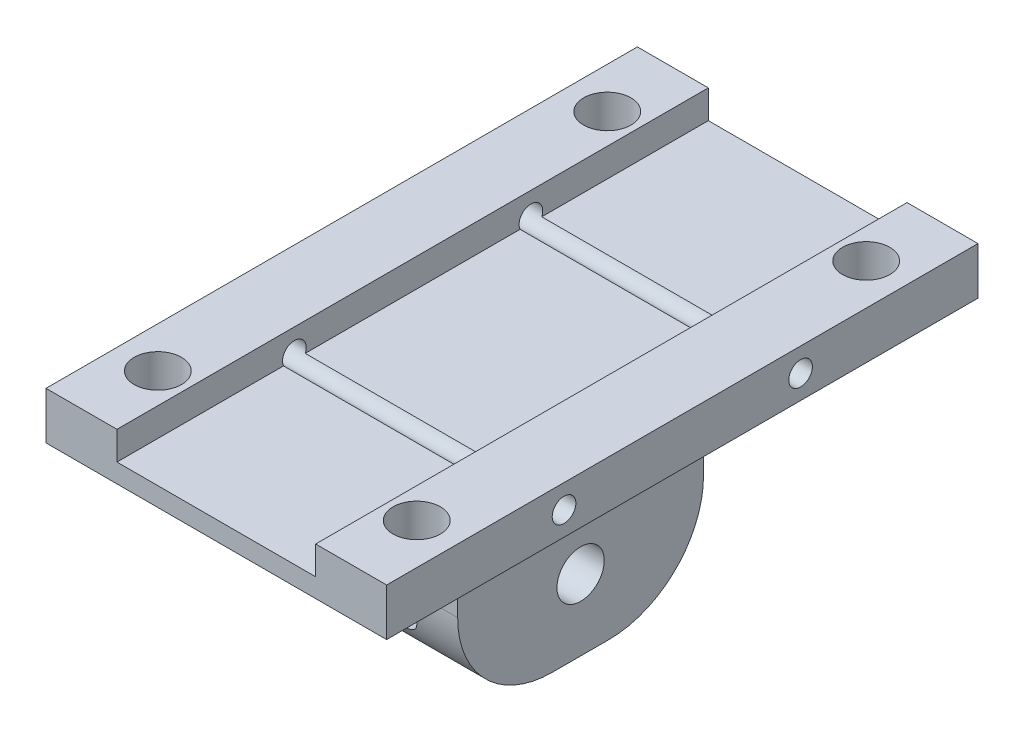
SolidWorks part; units mm, degrees
ref_plane "Front Plane" through (0, 0, 0) normal (0, 0, 1) x (1, 0, 0)
ref_plane "Top Plane" through (0, 0, 0) normal (0, 1, 0) x (1, 0, 0)
ref_plane "Right Plane" through (0, 0, 0) normal (1, 0, 0) x (0, 0, -1)
sketch "Sketch1" plane through (0, 0, 0) normal (1, 0, 0) x (0, 0, -1)
  line L0 (25.9808, -15) -> (25.9808, 15)
  line L1 (25.9808, 15) -> (-25.9808, 15)
  line L2 (-25.9808, 15) -> (-25.9808, -15)
  line L3 (-25.9808, -15) -> (25.9808, -15)
  circle A0 centre (0, 0) radius 5
extrude "Boss-Extrude1" add sketch "Sketch1" along normal mid plane 29
sketch "Sketch2" plane through (0, 15, 0) normal (0, 1, 0) x (1, 0, 0)
  line L4 (-14.5, 25.9808) -> (-14.5, -25.9808)
  line L5 (-14.5, -25.9808) -> (14.5, -25.9808)
  line L6 (14.5, -25.9808) -> (14.5, 25.9808)
  line L7 (14.5, 25.9808) -> (-14.5, 25.9808)
  line L8 (-14.5, 25.9808) -> (-14.5, -25.9808)
  line L9 (-14.5, -25.9808) -> (14.5, -25.9808)
  line L10 (14.5, -25.9808) -> (14.5, 25.9808)
  line L11 (14.5, 25.9808) -> (-14.5, 25.9808)
  dimension "D1" = 0
extrude "Boss-Extrude2" add sketch "Sketch2" along normal blind 15
sketch "Sketch3" plane through (0, 30, 0) normal (0, 1, 0) x (1, 0, 0)
  line L1 (-36, -62.5) -> (36, -62.5)
  line L2 (-36, -62.5) -> (-36, 62.5)
  line L3 (-36, 62.5) -> (36, 62.5)
  line L4 (36, -62.5) -> (36, 62.5)
  line L5 (-36, -62.5) -> (36, 62.5) construction
  line L6 (-36, 62.5) -> (36, -62.5) construction
  line L7 (-27.36, -47.5) -> (27.36, -47.5) construction
  line L8 (-27.36, -47.5) -> (-27.36, 47.5) construction
  line L9 (-27.36, 47.5) -> (27.36, 47.5) construction
  line L10 (27.36, -47.5) -> (27.36, 47.5) construction
  line L11 (-27.36, -47.5) -> (27.36, 47.5) construction
  line L12 (-27.36, 47.5) -> (27.36, -47.5) construction
  circle A0 centre (-27.36, 47.5) radius 5
  circle A1 centre (27.36, 47.5) radius 5
  circle A2 centre (-27.36, -47.5) radius 5
  circle A3 centre (27.36, -47.5) radius 5
  point P0 (0, 0)
  point P6 (0, 0)
  dimension "D1" = 10
  dimension "D2" = 72
  dimension "D3" = 125
  dimension "D4" = 15
extrude "Boss-Extrude3" add sketch "Sketch3" along normal blind 10
fillet "Fillet1" radius 20 2 edges at (0, -15, -25.9808) (0, -15, 25.9808)
sketch "Sketch4" plane through (0, 0, 0) normal (0, 0, 1) x (1, 0, 0)
  circle A0 centre (0, 0) radius 5
  dimension "D1" = 10
extrude "Cut-Extrude1" cut sketch "Sketch4" against normal through all both and the other way through all
sketch "Sketch5" plane through (0, 0, 62.5) normal (0, 0, 1) x (1, 0, 0)
  line L0 (-36, 40) -> (36, 40) construction
  line L1 (-21, 40) -> (21, 40)
  line L2 (-21, 40) -> (-21, 34)
  line L3 (-21, 34) -> (21, 34)
  line L4 (21, 40) -> (21, 34)
  point P6 (0, 34)
  dimension "D1" = 42
  dimension "D2" = 6
extrude "Cut-Extrude2" cut sketch "Sketch5" against normal through all both and the other way through all
sketch "Sketch6" plane through (36, 0, 0) normal (1, 0, 0) x (0, 0, -1)
  line L0 (-25, 35) -> (25, 35) construction
  line L1 (-62.5, 40) -> (62.5, 40) construction
  circle A0 centre (-25, 35) radius 2.5
  circle A1 centre (25, 35) radius 2.5
  point P4 (0, 35)
  dimension "D1" = 5
  dimension "D2" = 50
  dimension "D3" = 5
extrude "Cut-Extrude3" cut sketch "Sketch6" against normal through all both and the other way through all
